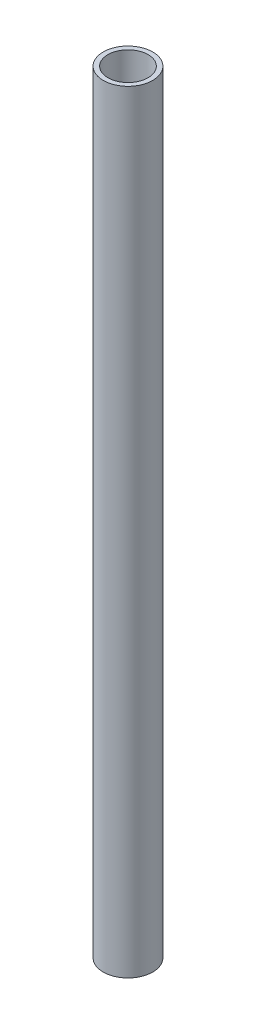
SolidWorks part; units mm, degrees
ref_plane "Front Plane" through (0, 0, 0) normal (0, 0, 1) x (1, 0, 0)
ref_plane "Top Plane" through (0, 0, 0) normal (0, 1, 0) x (1, 0, 0)
ref_plane "Right Plane" through (0, 0, 0) normal (1, 0, 0) x (0, 0, -1)
sketch "Sketch1" plane through (0, 0, 0) normal (0, 1, 0) x (1, 0, 0)
  circle A0 centre (0, 0) radius 6.5
  circle A1 centre (0, 0) radius 8
  dimension "D1" = 13
  dimension "D2" = 16
extrude "Boss-Extrude1" add sketch "Sketch1" along normal blind 250
